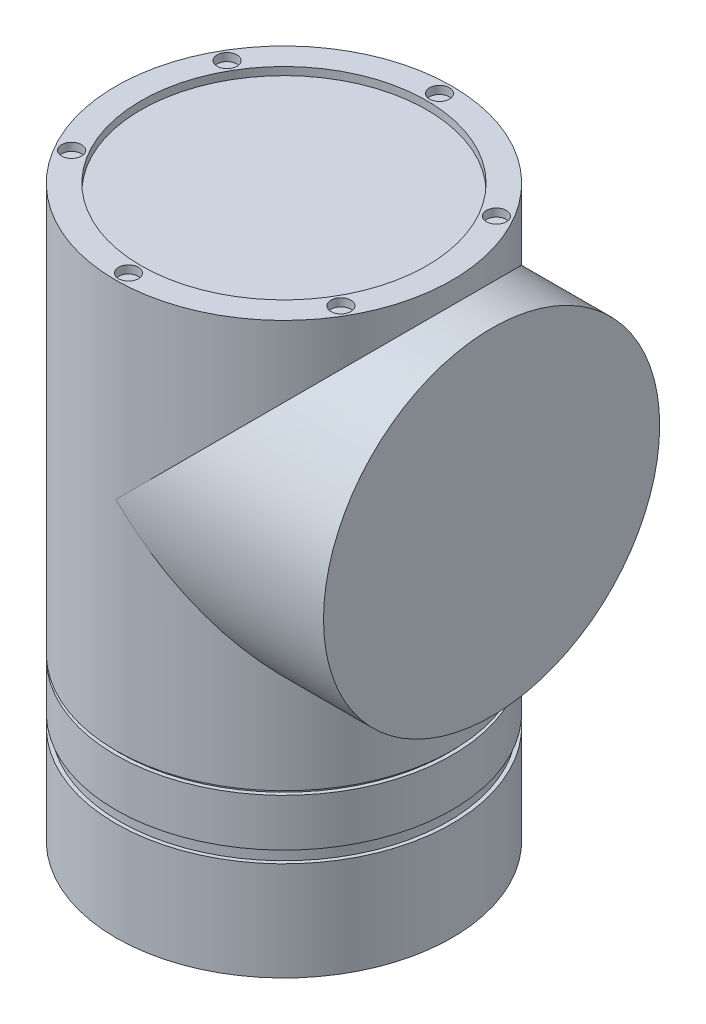
SolidWorks part; units mm, degrees
ref_plane "Alzado" through (0, 0, 0) normal (0, 0, 1) x (1, 0, 0)
ref_plane "Planta" through (0, 0, 0) normal (0, 1, 0) x (1, 0, 0)
ref_plane "Vista lateral" through (0, 0, 0) normal (1, 0, 0) x (0, 0, -1)
sketch "Croquis1" plane through (0, 0, 0) normal (0, 1, 0) x (1, 0, 0)
  circle A0 centre (0, 0) radius 42.5
  dimension "D1" = 85
extrude "Saliente-Extruir1" add sketch "Croquis1" along normal blind 142
sketch "Croquis2" plane through (0, 0, 0) normal (1, 0, 0) x (0, 0, -1)
  line L0 (42.5, 142) -> (-42.5, 142) construction
  line L2 (42.5, 0) -> (42.5, 142) construction
  circle A0 centre (0, 96) radius 42.5
  dimension "D1" = 85
  dimension "D2" = 46
  dimension "D3" = 42.5
extrude "Saliente-Extruir2" add sketch "Croquis2" along normal blind 52.5
sketch "Croquis3" plane through (0, 142, 0) normal (0, 1, 0) x (1, 0, 0)
  circle A0 centre (0, 0) radius 42.5
  circle A1 centre (0, 0) radius 36.1436
  circle A2 centre (0, 39.3191) radius 2.5082
  circle A3 centre (34.0513, 19.6595) radius 2.5082
  circle A4 centre (34.0513, -19.6595) radius 2.5082
  circle A5 centre (0, -39.3191) radius 2.5082
  circle A6 centre (-34.0513, -19.6595) radius 2.5082
  circle A7 centre (-34.0513, 19.6595) radius 2.5082
  point P18 (0, 0)
  dimension "D1" = 6
extrude "Saliente-Extruir3" add sketch "Croquis3" along normal blind 2
sketch "Croquis6" plane through (0, 0, 0) normal (0, -1, 0) x (1, 0, 0)
  circle A0 centre (0, 0) radius 42.5
  circle A1 centre (0, 0) radius 41.5461
extrude "Cortar-Extruir1" cut sketch "Croquis6" against normal blind 3 from offset 25 offset against normal yes
sketch "Croquis7" plane through (0, 0, 0) normal (0, -1, 0) x (-1, 0, 0)
  circle A0 centre (0, 0) radius 42.5
  circle A1 centre (0, 0) radius 41.5461
extrude "Cortar-Extruir2" cut sketch "Croquis7" against normal blind 1 from offset 40 offset against normal yes
sketch "Croquis8" plane through (0, 0, 0) normal (0, 0, 1) x (1, 0, 0)
  circle A1 centre (0, 12.3682) radius 7.3552
extrude "Cortar-Extruir3" cut sketch "Croquis8" against normal blind 21 from offset 30
